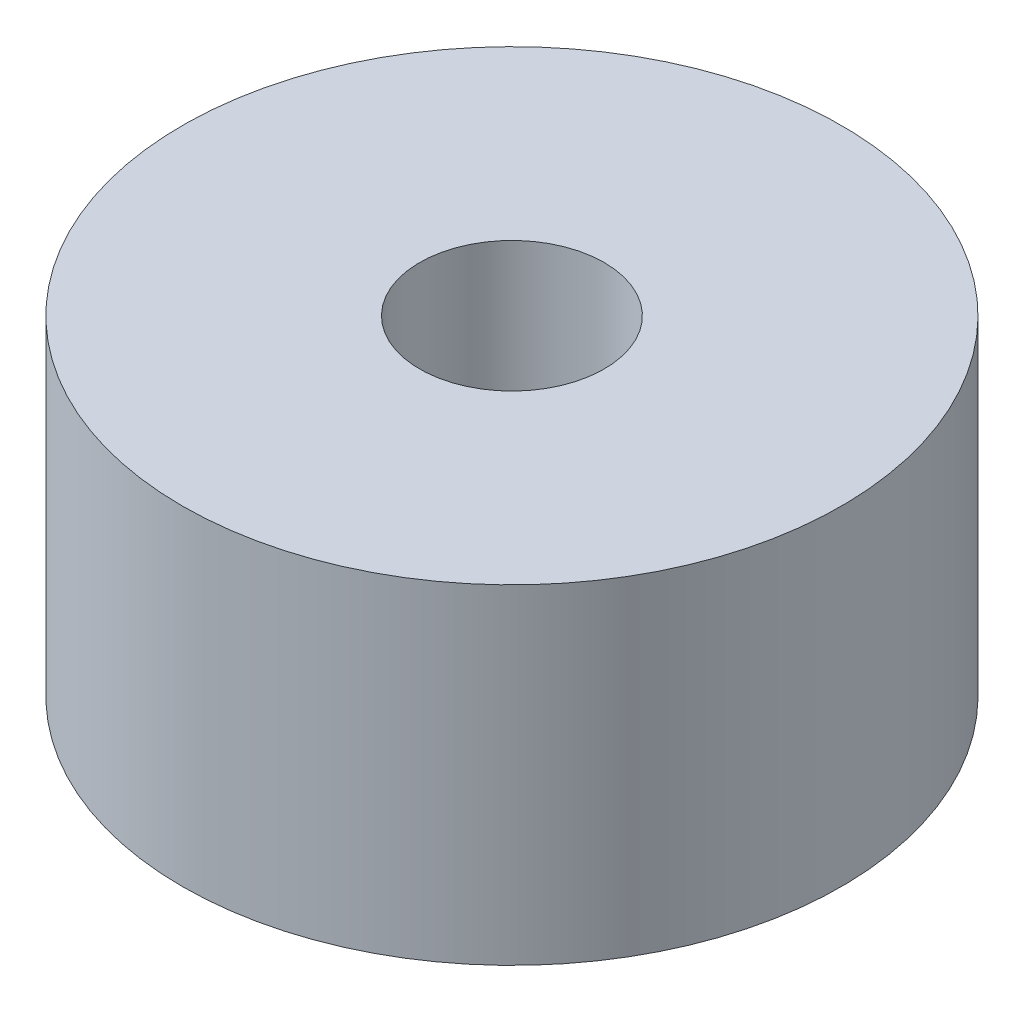
SolidWorks part; units mm, degrees
ref_plane "Plan de face" through (0, 0, 0) normal (0, 0, 1) x (1, 0, 0)
ref_plane "Plan de dessus" through (0, 0, 0) normal (0, 1, 0) x (1, 0, 0)
ref_plane "Plan de droite" through (0, 0, 0) normal (1, 0, 0) x (0, 0, -1)
sketch "Esquisse1" plane through (0, 0, 0) normal (0, 1, 0) x (1, 0, 0)
  circle A0 centre (0, 0) radius 5
  dimension "D1" = 10
extrude "Boss.-Extru.1" add sketch "Esquisse1" along normal blind 5
sketch "Esquisse2" plane through (0, 0, 0) normal (0, -1, 0) x (1, 0, 0)
  circle A0 centre (0, 0) radius 1.4
  dimension "D1" = 2.8
extrude "Enlèv. mat.-Extru.1" cut sketch "Esquisse2" against normal blind 7.7
